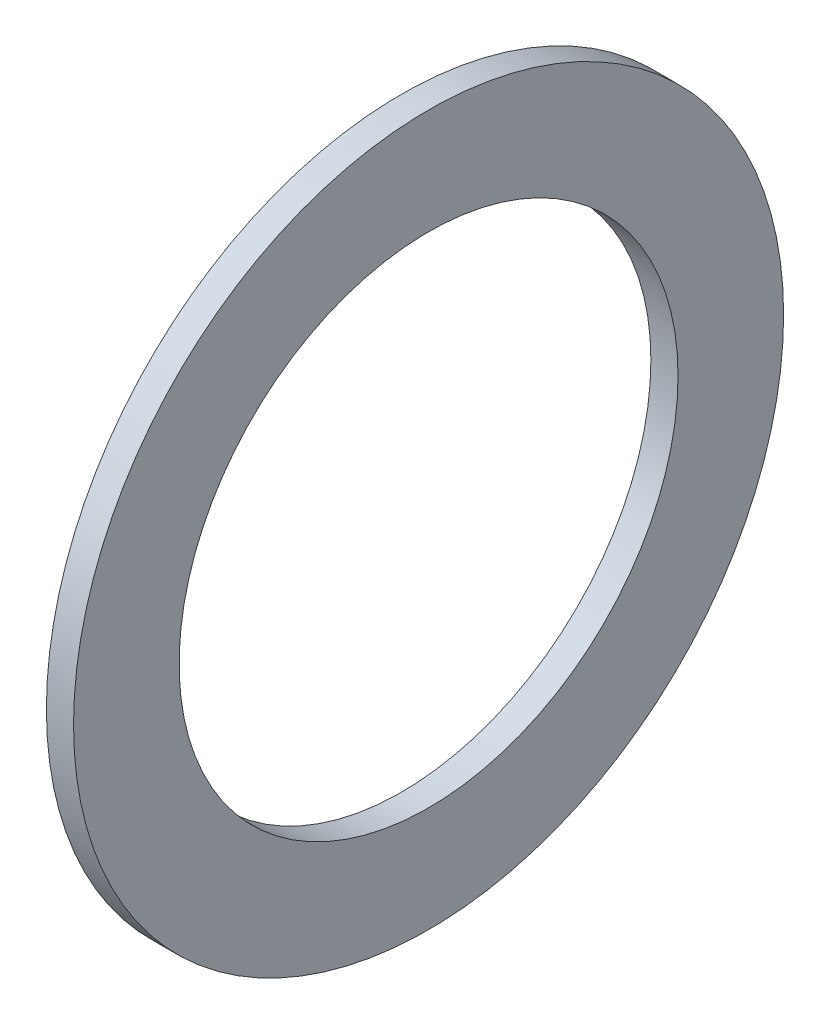
SolidWorks part; units mm, degrees
ref_plane "Front" through (0, 0, 0) normal (0, 0, 1) x (1, 0, 0)
ref_plane "Top" through (0, 0, 0) normal (0, 1, 0) x (1, 0, 0)
ref_plane "Right" through (0, 0, 0) normal (1, 0, 0) x (0, 0, -1)
sketch "Sketch1" plane through (0, 0, 0) normal (1, 0, 0) x (0, 0, -1)
  circle A1 centre (0, 0) radius 17
  circle A5 centre (0, 0) radius 11.945
  dimension "D1" = 5.055
  dimension "D2" = 23.89
extrude "Boss-Extrude1" add sketch "Sketch1" along normal mid plane 1.3
